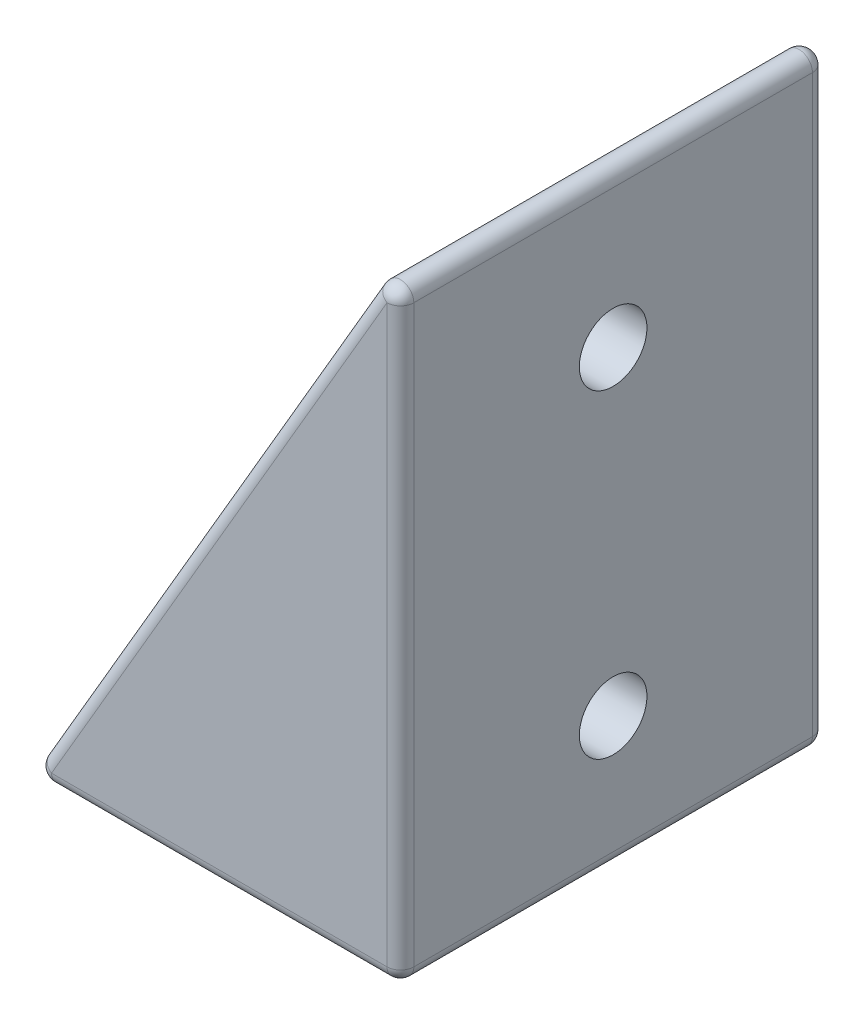
SolidWorks part; units mm, degrees
material "PET"
ref_plane "Front Plane" through (0, 0, 0) normal (0, 0, 1) x (1, 0, 0)
ref_plane "Top Plane" through (0, 0, 0) normal (0, 1, 0) x (1, 0, 0)
ref_plane "Right Plane" through (0, 0, 0) normal (1, 0, 0) x (0, 0, -1)
sketch "Sketch1" plane through (0, 0, 0) normal (0, 0, 1) x (1, 0, 0)
  line L0 (0, 0) -> (0, 38.1)
  line L1 (0, 38.1) -> (-22.225, 0)
  line L2 (-22.225, 0) -> (0, 0)
  dimension "D1" = 38.1
  dimension "D2" = 22.225
extrude "Boss-Extrude1" add sketch "Sketch1" along normal blind 25.4
fillet "Fillet1" radius 0.8 9 edges at (-11.1125, 0, 0) (0, 19.05, 0) (-11.1125, 19.05, 0) (-11.1125, 0, 25.4) (-11.1125, 19.05, 25.4) (-22.225, 0, 12.7) (0, 38.1, 12.7) (0, 0, 12.7) (0, 19.05, 25.4)
sketch "Sketch2" plane through (0, 0, 0) normal (1, 0, 0) x (0, 0, -1)
  line L0 (-0.8, 35.1409) -> (-24.6, 35.1409) construction
  circle A0 centre (-12.7, 26.8859) radius 2.0193
  circle A1 centre (-12.7, 7.8359) radius 2.0193
  point P6 (-12.7, 35.1409)
  dimension "D1" = 4.0386
  dimension "D2" = 8.255
  dimension "D3" = 19.05
extrude "Cut-Extrude1" cut sketch "Sketch2" against normal blind 50.8
